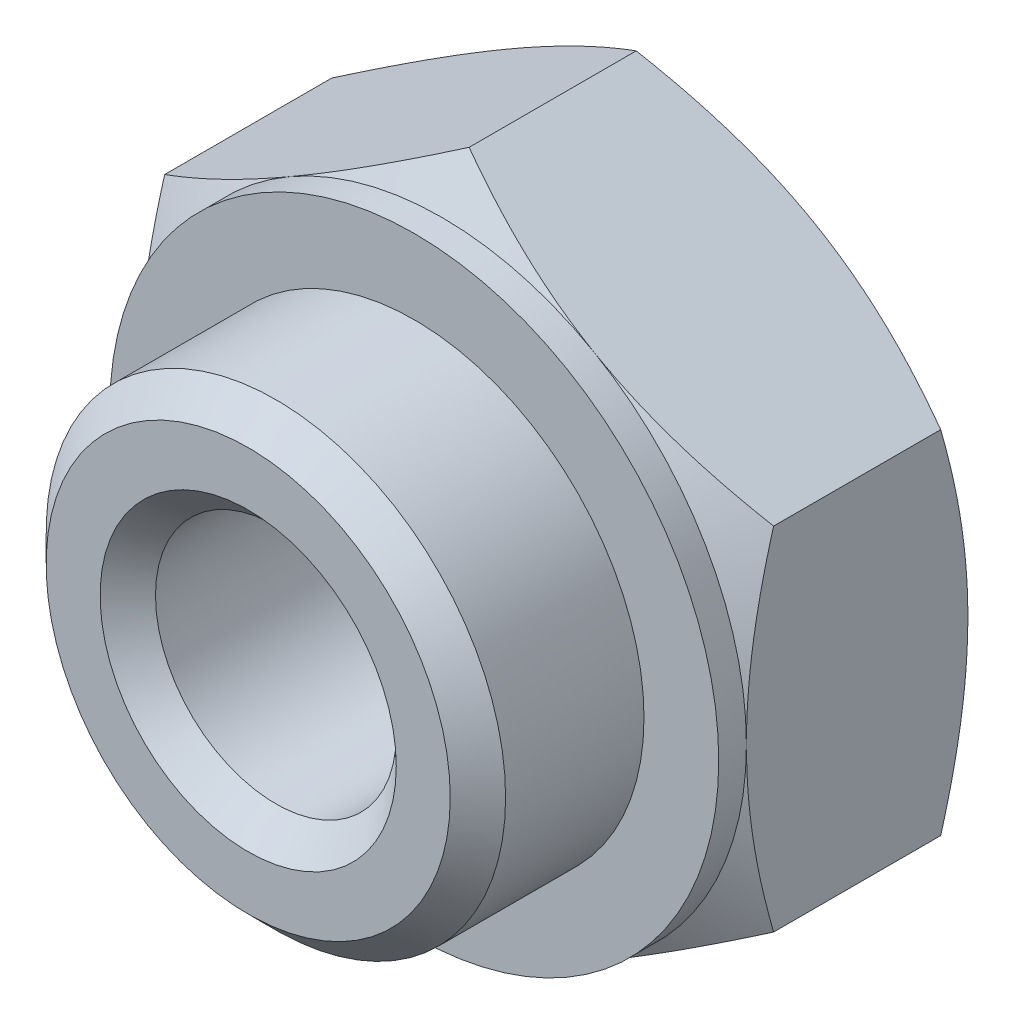
SolidWorks part; units mm, degrees
ref_plane "Płaszczyzna przednia" through (0, 0, 0) normal (0, 0, 1) x (1, 0, 0)
ref_plane "Płaszczyzna górna" through (0, 0, 0) normal (0, 1, 0) x (1, 0, 0)
ref_plane "Płaszczyzna prawa" through (0, 0, 0) normal (1, 0, 0) x (0, 0, -1)
sketch "Sketch1" plane through (0, 0, 0) normal (0, 0, 1) x (1, 0, 0)
  line L1 (-11, 6.3509) -> (-11, -6.3509)
  line L2 (-11, -6.3509) -> (0, -12.7017)
  line L3 (0, -12.7017) -> (11, -6.3509)
  line L4 (11, -6.3509) -> (11, 6.3509)
  line L5 (11, 6.3509) -> (0, 12.7017)
  line L6 (0, 12.7017) -> (-11, 6.3509)
  circle A0 centre (0, 0) radius 11 construction
  circle A1 centre (0, 0) radius 4.35
  dimension "D1" = 22
  dimension "D2" = 8.7
extrude "Boss-Extrude1" add sketch "Sketch1" along normal blind 8
sketch "Sketch2" plane through (0, 0, 8) normal (0, 0, 1) x (1, 0, 0)
  circle A0 centre (0, 0) radius 11
  circle A1 centre (0, 0) radius 4.35
extrude "Boss-Extrude2" add sketch "Sketch2" along normal blind 1
sketch "Sketch3" plane through (0, 0, 9) normal (0, 0, 1) x (1, 0, 0)
  circle A0 centre (0, 0) radius 4.35
  circle A1 centre (0, 0) radius 8.3
  dimension "D1" = 16.6
extrude "Boss-Extrude3" add sketch "Sketch3" along normal blind 6
sketch "Szkic9" plane through (0, 0, 0) normal (0, 0, -1) x (-1, 0, 0)
  circle A0 centre (0, 0) radius 11
extrude "Wytnij-wyciągnięcie3" cut sketch "Szkic9" against normal blind 1 draft 60 flip side to cut
sketch "Szkic10" plane through (0, 0, 8) normal (0, 0, 1) x (1, 0, 0)
  circle A0 centre (0, 0) radius 11
extrude "Wytnij-wyciągnięcie4" cut sketch "Szkic10" against normal blind 1 draft 60 flip side to cut
sketch "Szkic11" plane through (0, 0, 0) normal (0, 0, -1) x (-1, 0, 0)
  circle A1 centre (0, 0) radius 5.35
extrude "Wytnij-wyciągnięcie5" cut sketch "Szkic11" against normal blind 1 draft 60
sketch "Szkic13" plane through (0, 0, 15) normal (0, 0, 1) x (1, 0, 0)
  circle A0 centre (0, 0) radius 5.35
  circle A1 centre (0, 0) radius 7.3
extrude "Wytnij-wyciągnięcie8" cut sketch "Szkic13" against normal blind 1 draft 45 flip side to cut
